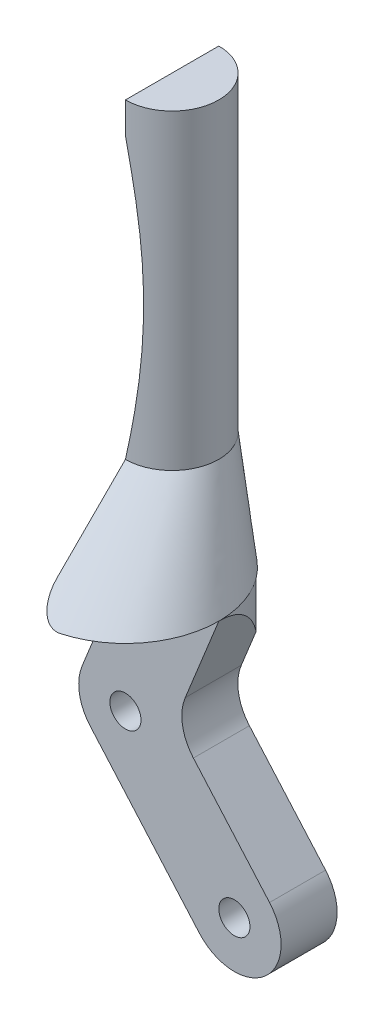
SolidWorks part; units mm, degrees
ref_plane "前视基准面" through (0, 0, 0) normal (0, 0, 1) x (1, 0, 0)
ref_plane "上视基准面" through (0, 0, 0) normal (0, 1, 0) x (1, 0, 0)
ref_plane "右视基准面" through (0, 0, 0) normal (1, 0, 0) x (0, 0, -1)
sketch "草图1" plane through (0, 0, 0) normal (0, 1, 0) x (1, 0, 0)
  line L0 (0, 3) -> (0, -3)
  arc A0 (0, -3) -> (0, 3) centre (0, 0) ccw
  dimension "D1" = 6
ref_plane "基准面2" through (0, 3, 0) normal (0, 1, 0) x (1, 0, 0)
sketch "草图3" plane through (0, 3, 0) normal (0, 1, 0) x (1, 0, 0)
  line L0 (0, 0) -> (0, 3)
  arc A0 (0, 0) -> (0, 3) centre (0, 1.5) ccw
loft "放样2" add profiles "草图3", "草图1"
sketch "草图4" plane through (0, 3, 0) normal (0, 1, 0) x (1, 0, 0)
  line L0 (0, 3) -> (0, 0)
  arc A0 (0, 0) -> (0, 3) centre (0, 1.5) ccw
extrude "凸台-拉伸1" add sketch "草图4" along normal blind 10
sketch "草图5" plane through (0, 0, 0) normal (0, 0, 1) x (1, 0, 0)
  line L3 (-0.5, -4) -> (0.5, -4) construction
  line L5 (0, -4) -> (0.3182, -3.6143) construction
  line L6 (0, 0) -> (3, 0) construction
  line L9 (0, 3) -> (0, 0) construction
  line L17 (3.5, -8) -> (3.1707, -7.6237) construction
  line L20 (0.3293, -4.3763) -> (0, -4) construction
  line L21 (3.5, -8) -> (0, -4) construction
  line L22 (2.3711, -8.9878) -> (-1.1289, -4.9878)
  line L23 (4.6289, -7.0122) -> (2.183, -4.2169)
  line L24 (0, 0) -> (-1.3905, -3.4375)
  line L25 (3, 0) -> (1.9213, -2.6667)
  line L26 (0, 0) -> (3, 0)
  circle A0 centre (0, -4) radius 0.5
  circle A2 centre (3.5, -8) radius 0.5
  arc A10 (2.3711, -8.9878) -> (4.6289, -7.0122) centre (3.5, -8) ccw
  arc A11 (-1.3905, -3.4375) -> (-1.1289, -4.9878) centre (0, -4) ccw
  arc A12 (2.183, -4.2169) -> (1.9213, -2.6667) centre (3.3118, -3.2292) cw
  point P2 (1.75, -6)
  point P4 (1.75, -6)
  dimension "D1" = 1
  dimension "D4" = 1.5
  dimension "D5" = 1
  dimension "D7" = 4
  dimension "D8" = 1.5
  dimension "D2" = 0
  dimension "D3" = 4
  dimension "D6" = 3.5
extrude "凸台-拉伸2" add sketch "草图5" against normal blind 1.8
fillet "圆角1" radius 0.8 1 edges
fillet "圆角2" radius 0.8 1 edges
sketch "草图9" plane through (0, 0, 0) normal (0, 0, 1) x (1, 0, 0)
  line L0 (0, 11.8467) -> (0, -5.3526) construction
  line L1 (-2.0887, 12) -> (3.6922, 12) construction
  line L2 (1.5, 13) -> (0, 13) construction
  line L3 (-2.7288, 3) -> (8.3976, 3) construction
  line L4 (3.3317, 3) -> (-3.3317, 3) construction
  line L5 (0.5, 14.8062) -> (0.5, 0.8982) construction
  line L6 (1.5, 3) -> (1.5, 13) construction
  line L7 (0, 12) -> (0, 3)
  arc A0 (0, 12) -> (0, 3) centre (-20, 7.5) cw
  dimension "D1" = 1
  dimension "D2" = 0
  dimension "D3" = 1
extrude "切除-拉伸5" cut sketch "草图9" against normal through all
fillet "圆角3" radius 0.5 2 edges at (0.4432, 9.0247, -0.067) (0, 12, -1.5)
sketch "草图10" plane through (0, 0, 0) normal (0, -1, 0) x (1, 0, 0)
  line L0 (2.2008, -2.0393) -> (3.0124, -2.0393)
  line L1 (3.0124, -2.0393) -> (3.0004, 0)
  arc A0 (2.2008, -2.0393) -> (3.0004, 0) centre (0, 0) ccw
extrude "切除-拉伸7" cut sketch "草图10" along normal blind 3 contours A0 L0 L1
